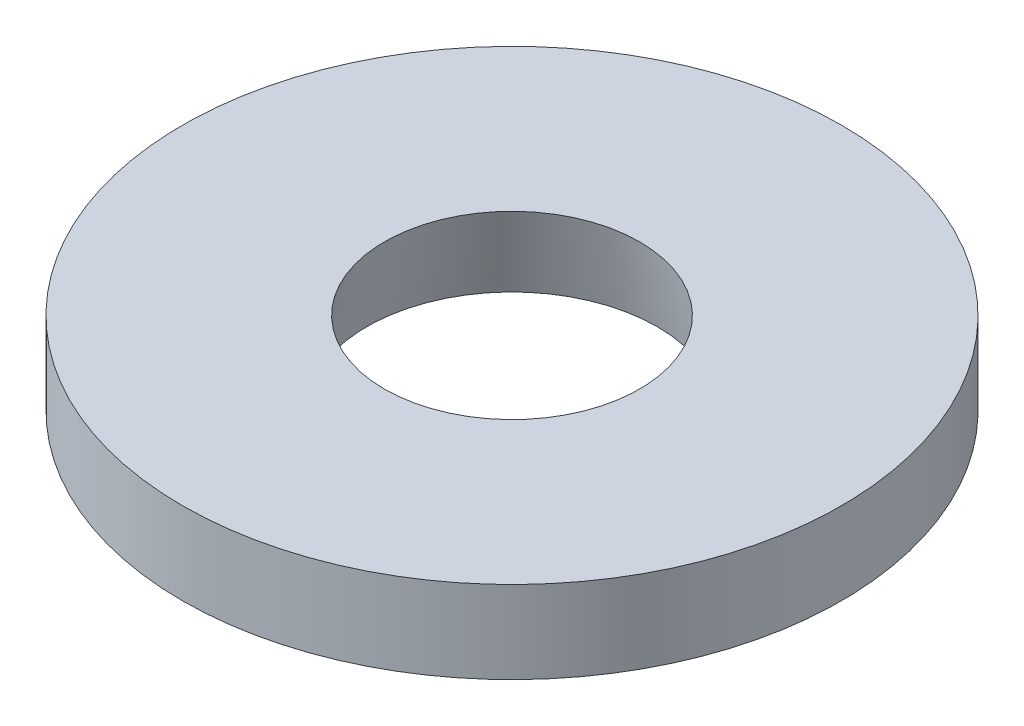
SolidWorks part; units mm, degrees
material "303 Stainless Steel"
ref_plane "Front Plane" through (0, 0, 0) normal (0, 0, 1) x (1, 0, 0)
ref_plane "Top Plane" through (0, 0, 0) normal (0, 1, 0) x (1, 0, 0)
ref_plane "Right Plane" through (0, 0, 0) normal (1, 0, 0) x (0, 0, -1)
sketch "Sketch1" plane through (0, 0, 0) normal (0, 1, 0) x (1, 0, 0)
  circle A0 centre (0, 0) radius 12.7
  circle A1 centre (0, 0) radius 3.556
  dimension "D1" = 7.112
  dimension "D2" = 25.4
extrude "Boss-Extrude1" add sketch "Sketch1" along normal blind 3.175
sketch "Sketch2" plane through (0, 0, 0) normal (0, 0, 1) x (1, 0, 0)
  line L0 (-3.556, 0) -> (3.556, 0) construction
  line L1 (-3.556, 0) -> (3.556, 0) construction
  line L2 (3.556, 0) -> (3.556, 3.175)
  line L5 (5.9372, -1.5875) -> (4.7466, 3.9688)
  line L6 (0, 0) -> (0, 3.3906) construction
  line L7 (3.556, 0) -> (3.556, -1.5875)
  line L9 (3.556, -1.5875) -> (5.9372, -1.5875)
  line L10 (3.556, 3.175) -> (3.556, 3.9688)
  line L11 (3.556, 3.175) -> (3.556, 3.9687) construction
  line L12 (3.556, 3.9688) -> (4.7466, 3.9688)
  line L13 (3.556, 3.175) -> (3.556, 74.2137) construction
  dimension "D1" = 3.175
  dimension "D2" = 1.5875
  dimension "D3" = 2.3813
  dimension "D4" = 0.7937
  dimension "D5" = 1.1906
revolve "Cut-Revolve1" cut sketch "Sketch2" angle 360 about L6
